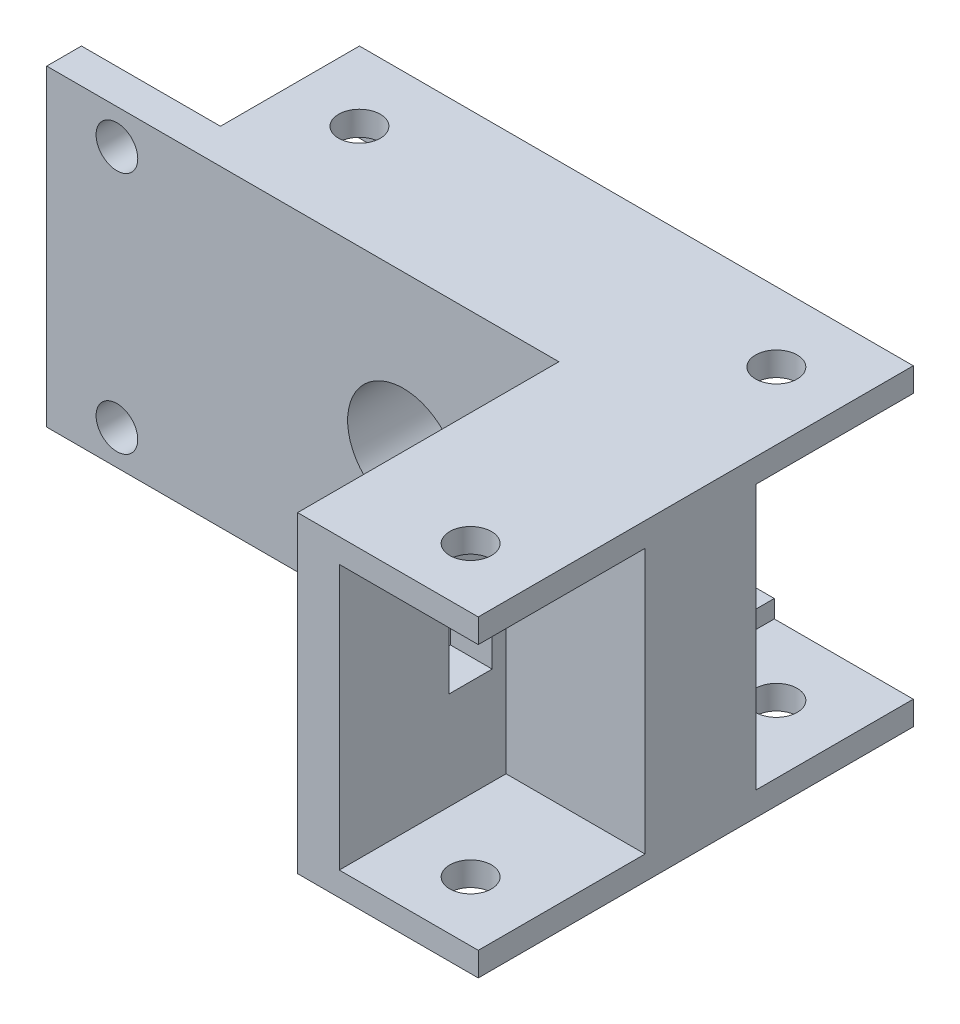
SolidWorks part; units mm, degrees
ref_plane "Front Plane" through (0, 0, 0) normal (0, 0, 1) x (1, 0, 0)
ref_plane "Top Plane" through (0, 0, 0) normal (0, 1, 0) x (1, 0, 0)
ref_plane "Right Plane" through (0, 0, 0) normal (1, 0, 0) x (0, 0, -1)
sketch "Sketch1" plane through (0, 0, 0) normal (0, 0, 1) x (1, 0, 0)
  line L1 (0, 0) -> (36.85, 0)
  line L2 (0, 0) -> (0, 22.5)
  line L3 (0, 22.5) -> (36.85, 22.5)
  line L4 (36.85, 0) -> (36.85, 22.5)
  dimension "D1" = 36.85
  dimension "D2" = 22.5
extrude "Boss-Extrude1" add sketch "Sketch1" along normal blind 2.5
sketch "Sketch2" plane through (36.85, 0, 0) normal (1, 0, 0) x (0, 0, -1)
  line L1 (0, 0) -> (-21.3, 0)
  line L2 (0, 0) -> (0, 22.5)
  line L3 (0, 22.5) -> (-21.3, 22.5)
  line L4 (-21.3, 0) -> (-21.3, 22.5)
  dimension "D1" = 22.5
  dimension "D2" = 21.3
extrude "Boss-Extrude2" add sketch "Sketch2" along normal blind 3
sketch "Sketch3" plane through (39.85, 0, 0) normal (1, 0, 0) x (0, 0, -1)
  line L0 (-21.3, 22.5) -> (-21.3, 0) construction
  line L1 (0, 0) -> (-21.3, 0)
  line L2 (0, 0) -> (0, 3)
  line L3 (0, 3) -> (-21.3, 3)
  line L4 (-21.3, 0) -> (-21.3, 3)
  dimension "D1" = 3
extrude "Boss-Extrude3" add sketch "Sketch3" along normal blind 10
sketch "Sketch4" plane through (0, 0, 0) normal (0, 0, -1) x (-1, 0, 0)
  line L1 (0, 0) -> (-49.85, 0)
  line L2 (0, 0) -> (0, 3)
  line L3 (0, 3) -> (-49.85, 3)
  line L4 (-49.85, 0) -> (-49.85, 3)
extrude "Boss-Extrude4" add sketch "Sketch4" along normal blind 10
sketch "Sketch8" plane through (39.85, 0, 0) normal (1, 0, 0) x (0, 0, -1)
  line L0 (-21.3, 22.5) -> (-21.3, 3) construction
  line L1 (-13.4, 13.75) -> (-10.3, 13.75)
  line L2 (-13.4, 13.75) -> (-13.4, 8.75)
  line L3 (-13.4, 8.75) -> (-10.3, 8.75)
  line L4 (-10.3, 13.75) -> (-10.3, 8.75)
  line L5 (-21.3, 0) -> (-2.5, 0) construction
  dimension "D1" = 3.1
  dimension "D2" = 5
  dimension "D3" = 7.9
  dimension "D4" = 8.75
extrude "Cut-Extrude1" cut sketch "Sketch8" against normal blind 5
sketch "Sketch9" plane through (0, 0, 2.5) normal (0, 0, 1) x (1, 0, 0)
  line L0 (36.85, 0) -> (36.85, 22.5) construction
  line L1 (0, 0) -> (36.85, 0) construction
  circle A0 centre (25.65, 11.25) radius 4
  circle A1 centre (5.05, 20) radius 1.5
  circle A2 centre (5.05, 2.5) radius 1.5
  point P8 (0, 0)
  point P9 (0, 0)
  dimension "D1" = 8
  dimension "D5" = 3
  dimension "D6" = 3
  dimension "D2" = 11.2
  dimension "D3" = 31.8
  dimension "D4" = 17.5
  dimension "D7" = 2.5
  dimension "D8" = 11.25
extrude "Cut-Extrude2" cut sketch "Sketch9" against normal blind 25
sketch "Sketch11" plane through (0, 0, -10) normal (0, 0, -1) x (-1, 0, 0)
  line L0 (-6.4642, 3) -> (-39.85, 3) construction
  line L1 (0, 0) -> (-10, 0)
  line L2 (0, 0) -> (0, 3)
  line L3 (0, 3) -> (-10, 3)
  line L4 (-10, 0) -> (-10, 3)
  dimension "D1" = 10
extrude "Cut-Extrude3" cut sketch "Sketch11" against normal blind 10
sketch "Sketch12" plane through (0, 3, 0) normal (0, 1, 0) x (1, 0, 0)
  line L0 (10, 0) -> (10, 10) construction
  line L2 (10, 10) -> (49.85, 10) construction
  circle A0 centre (15, 5) radius 1.5
  circle A1 centre (45, 5) radius 1.5
  circle A2 centre (45, -17) radius 1.5
  point P6 (0, 0)
  point P7 (0, 0)
  point P8 (0, 0)
  point P13 (0, 0)
  dimension "D1" = 3
  dimension "D2" = 30
  dimension "D3" = 22
  dimension "D4" = 5
  dimension "D5" = 5
extrude "Cut-Extrude4" cut sketch "Sketch12" against normal blind 10
sketch "Sketch14" plane through (0, 3, 0) normal (0, 1, 0) x (1, 0, 0)
  line L0 (10, 10) -> (49.85, 10) construction
  line L1 (20, 10) -> (32.5, 10)
  line L2 (20, 10) -> (20, 0)
  line L3 (20, 0) -> (32.5, 0)
  line L4 (32.5, 10) -> (32.5, 0)
  line L5 (10, 0) -> (39.85, 0) construction
  line L6 (39.85, 0) -> (39.85, -21.3) construction
  line L7 (39.85, -1.3) -> (49.85, -1.3)
  line L8 (39.85, -1.3) -> (39.85, -9.3)
  line L9 (39.85, -9.3) -> (49.85, -9.3)
  line L10 (49.85, -1.3) -> (49.85, -9.3)
  line L11 (49.85, 10) -> (49.85, -21.3) construction
  line L12 (10, 0) -> (10, 10) construction
  line L13 (49.85, -21.3) -> (39.85, -21.3) construction
  dimension "D1" = 12.5
  dimension "D2" = 10
  dimension "D3" = 8
  dimension "D4" = 12
extrude "Boss-Extrude8" add sketch "Sketch14" along normal up to vertex (19.5 mm away)
sketch "Sketch13" plane through (0, 22.5, 0) normal (0, 1, 0) x (1, 0, 0)
  line L0 (49.85, 10) -> (49.85, -1.3) construction
  line L1 (10, 10) -> (49.85, 10)
  line L2 (10, 10) -> (10, 0)
  line L3 (10, 0) -> (39.85, 0)
  line L4 (49.85, 10) -> (49.85, 0)
  line L7 (49.85, 0) -> (49.85, -21.3)
  line L8 (49.85, -21.3) -> (39.85, -21.3)
  line L9 (39.85, 0) -> (39.85, -21.3)
  circle A0 centre (15, 5) radius 1.5
  circle A1 centre (45, 5) radius 1.5
  circle A2 centre (45, -17) radius 1.5
extrude "Boss-Extrude7" add sketch "Sketch13" against normal blind 3
sketch "Sketch15" plane through (0, 0, 2.5) normal (0, 0, 1) x (1, 0, 0)
  circle A0 centre (25.65, 11.25) radius 4
extrude "Cut-Extrude5" cut sketch "Sketch15" against normal blind 43
sketch "Sketch16" plane through (0, 19.5, 0) normal (0, -1, 0) x (1, 0, 0)
  line L0 (10, 0) -> (10, -10) construction
  line L1 (10, -2.75) -> (20, -2.75)
  line L2 (10, -2.75) -> (10, -7.25)
  line L3 (10, -7.25) -> (20, -7.25)
  line L4 (20, -2.75) -> (20, -7.25)
  line L5 (49.85, -10) -> (10, -10) construction
  dimension "D1" = 10
  dimension "D2" = 4.5
  dimension "D3" = 2.75
extrude "Cut-Extrude6" cut sketch "Sketch16" against normal blind 1.25 and the other way blind 17.7525
sketch "Sketch17" plane through (49.85, 0, 0) normal (1, 0, 0) x (0, 0, -1)
  line L0 (-21.3, 22.5) -> (10, 22.5) construction
  line L1 (-23.4313, 20.775) -> (-9.3, 20.775)
  line L2 (-23.4313, 20.775) -> (-23.4313, 1.725)
  line L3 (-23.4313, 1.725) -> (-9.3, 1.725)
  line L4 (11.9346, 20.775) -> (11.9346, 1.725)
  line L7 (-9.3, 20.775) -> (-9.3, 1.725)
  line L8 (-1.3, 20.775) -> (-1.3, 1.725)
  line L9 (-9.3, 19.5) -> (-9.3, 3) construction
  line L10 (-1.3, 19.5) -> (-1.3, 3) construction
  line L11 (-1.3, 1.725) -> (11.9346, 1.725)
  line L12 (-1.3, 20.775) -> (11.9346, 20.775)
  dimension "D1" = 19.05
  dimension "D2" = 1.725
extrude "Cut-Extrude7" cut sketch "Sketch17" against normal up to vertex (10 mm away)
equation "\"D2@Sketch2\"=18.8+2.5"
